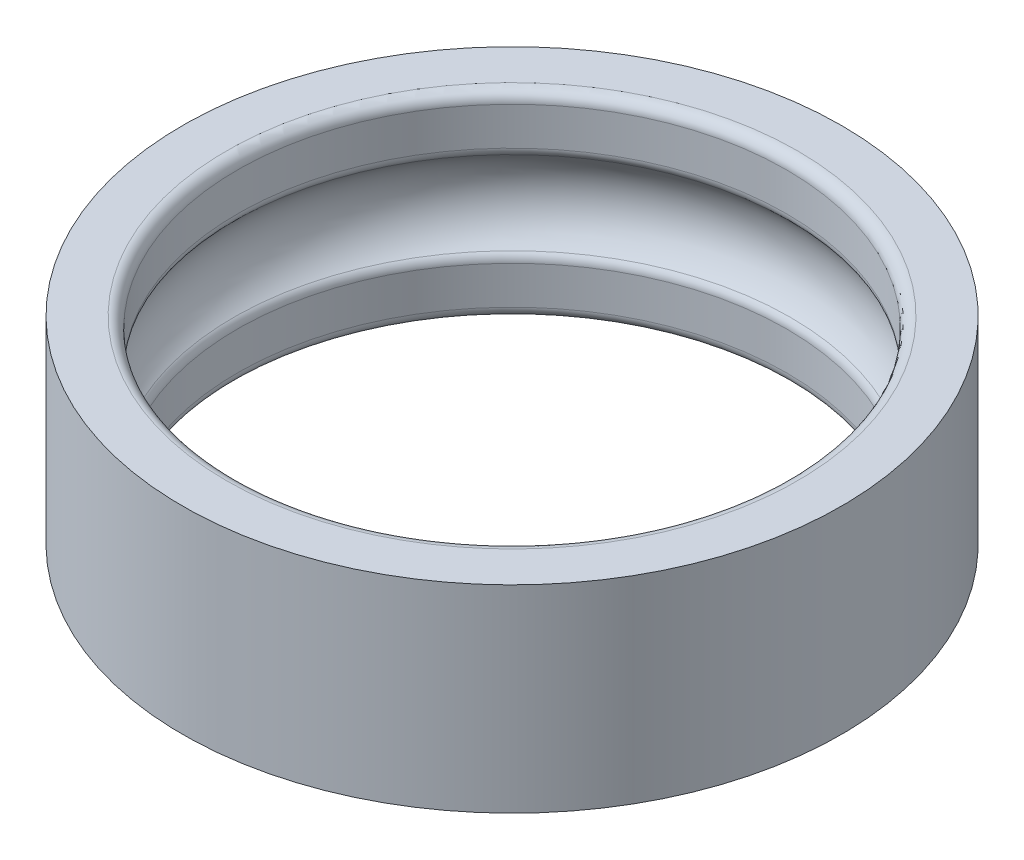
SolidWorks part; units mm, degrees
ref_plane "Front Plane" through (0, 0, 0) normal (0, 0, 1) x (1, 0, 0)
ref_plane "Top Plane" through (0, 0, 0) normal (0, 1, 0) x (1, 0, 0)
ref_plane "Right Plane" through (0, 0, 0) normal (1, 0, 0) x (0, 0, -1)
sketch "Sketch1" plane through (0, 0, 0) normal (1, 0, 0) x (0, 0, -1)
  line L0 (0, 0) -> (0, 22.6339) construction
  line L1 (25, -8) -> (25, -4.539)
  line L2 (26, 9) -> (30, 9)
  line L4 (30, 9) -> (30, -9)
  line L5 (30, -9) -> (26, -9)
  line L6 (25, 0) -> (7.4586, 0) construction
  line L7 (25, 0) -> (27.05, 0) construction
  line L8 (25, 4.539) -> (25, 8)
  arc A0 (25.3388, -3.7888) -> (25.3388, 3.7888) centre (22, 0) ccw
  arc A1 (25.3388, 3.7888) -> (25, 4.539) centre (26, 4.539) cw
  arc A2 (25.3388, -3.7888) -> (25, -4.539) centre (26, -4.539) ccw
  arc A3 (25, -8) -> (26, -9) centre (26, -8) ccw
  arc A6 (25, 8) -> (26, 9) centre (26, 8) cw
  point P6 (0, 0)
  point P8 (0, 0)
  point P15 (25, 4.0623)
  dimension "D4" = 10.1
  dimension "D6" = 1
  dimension "D1" = 18
  dimension "D2" = 30
  dimension "D3" = 5
  dimension "D5" = 22
revolve "Revolve1" add sketch "Sketch1" angle 360 about L0
scale "Scale1" scale about centroid uniform scaling yes scale factor 0.266667
